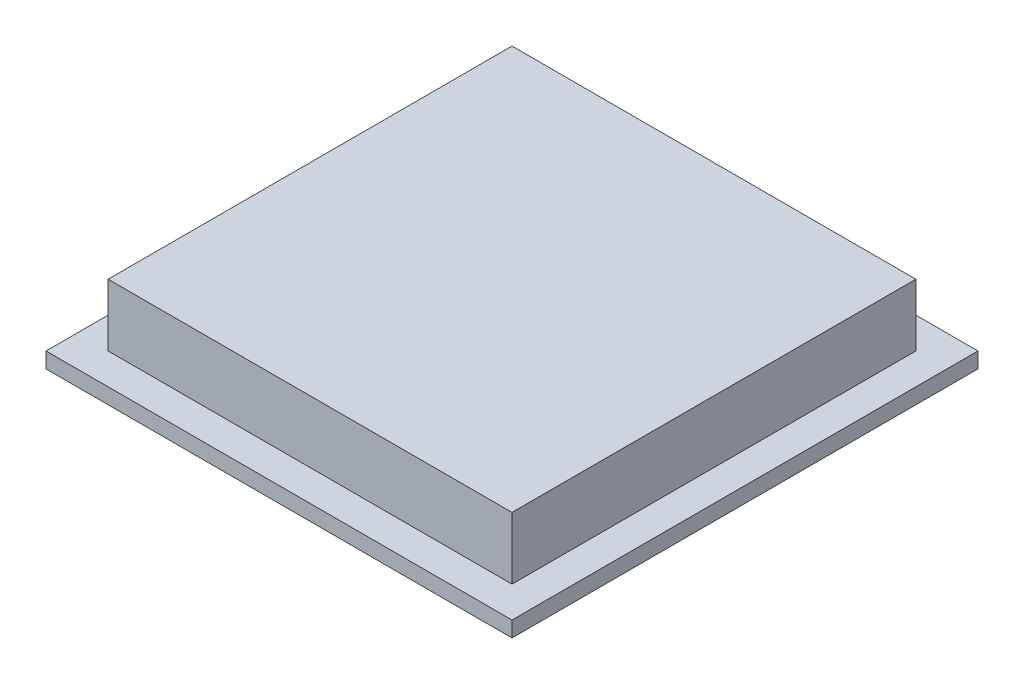
SolidWorks part; units mm, degrees
ref_plane "Front Plane" through (0, 0, 0) normal (0, 0, 1) x (1, 0, 0)
ref_plane "Top Plane" through (0, 0, 0) normal (0, 1, 0) x (1, 0, 0)
ref_plane "Right Plane" through (0, 0, 0) normal (1, 0, 0) x (0, 0, -1)
sketch "Sketch1" plane through (0, 0, 0) normal (0, 1, 0) x (1, 0, 0)
  line L1 (-19.05, -19.05) -> (19.05, -19.05)
  line L2 (-19.05, -19.05) -> (-19.05, 19.05)
  line L3 (-19.05, 19.05) -> (19.05, 19.05)
  line L4 (19.05, -19.05) -> (19.05, 19.05)
  line L5 (-19.05, -19.05) -> (19.05, 19.05) construction
  line L6 (-19.05, 19.05) -> (19.05, -19.05) construction
  point P0 (0, 0)
  dimension "D1" = 38.1
  dimension "D2" = 38.1
extrude "Boss-Extrude1" add sketch "Sketch1" along normal blind 6.35
sketch "Sketch2" plane through (0, 6.35, 0) normal (0, 1, 0) x (1, 0, 0)
  line L0 (-19.05, -19.05) -> (19.05, -19.05) construction
  line L1 (-19.05, 19.05) -> (-16.51, 19.05)
  line L2 (-19.05, 19.05) -> (-19.05, -19.05)
  line L3 (-19.05, -19.05) -> (-16.51, -19.05)
  line L4 (-16.51, 16.51) -> (-16.51, -16.51)
  line L6 (19.05, -19.05) -> (-19.05, -19.05)
  line L7 (19.05, -19.05) -> (19.05, -16.51)
  line L8 (16.51, -16.51) -> (-16.51, -16.51)
  line L9 (-19.05, -19.05) -> (-19.05, -16.51)
  line L10 (19.05, 19.05) -> (16.51, 19.05)
  line L11 (19.05, 19.05) -> (19.05, -19.05)
  line L12 (19.05, -19.05) -> (16.51, -19.05)
  line L13 (16.51, 16.51) -> (16.51, -16.51)
  line L14 (-19.05, 19.05) -> (19.05, 19.05)
  line L15 (-19.05, 19.05) -> (-19.05, 16.51)
  line L16 (-16.51, 16.51) -> (16.51, 16.51)
  line L17 (19.05, 19.05) -> (19.05, 16.51)
  line M11 (19.05, -19.05) -> (19.05, 19.05)
  line M12 (19.05, 19.05) -> (-19.05, 19.05)
  line M13 (-19.05, 19.05) -> (-19.05, -19.05)
  line M14 (-19.05, -19.05) -> (19.05, -19.05)
  dimension "D1" = 2.54
  dimension "D2" = 2.54
  dimension "D3" = 2.54
  dimension "D4" = 2.54
extrude "Cut-Extrude1" cut sketch "Sketch2" against normal blind 5.08 contours L6 L11 L2 L4 L16 L13 L8 M14 M11 M12 M13
sketch "Sketch3" plane through (0, 0, 0) normal (0, -1, 0) x (1, 0, 0)
  line L0 (-10.3216, 0) -> (10.3216, 0) construction
  circle A0 centre (0, 0) radius 8.1966
  ellipse E0 centre (0, 0) end of major axis (10.3216, 0) minor radius 8.1966
extrude "Cut-Extrude2" [suppressed] cut sketch "Sketch3" against normal blind 1.905 contours L0 E0
fillet "Fillet3" [suppressed] radius 2.032
fillet "Fillet4" [suppressed] radius 2.032
sketch "Sketch4" plane through (0, 0, 0) normal (0, -1, 0) x (1, 0, 0)
  circle A0 centre (0, 0) radius 8.1966
extrude "Cut-Extrude4" [suppressed] cut sketch "Sketch4" against normal blind 5.08
fillet "Fillet5" [suppressed] radius 2.032
fillet "Fillet6" [suppressed] radius 2.032
sketch "Sketch5" plane through (0, 0, 0) normal (0, -1, 0) x (1, 0, 0)
  circle A0 centre (0, 0) radius 10.755
  dimension "D1" = 21.51
extrude "Cut-Extrude5" cut sketch "Sketch5" against normal blind 5.08
fillet "Fillet7" radius 2.032 1 edges at (0, 5.08, -10.755)
fillet "Fillet8" radius 2.032 1 edges at (0, 0, -10.755)
